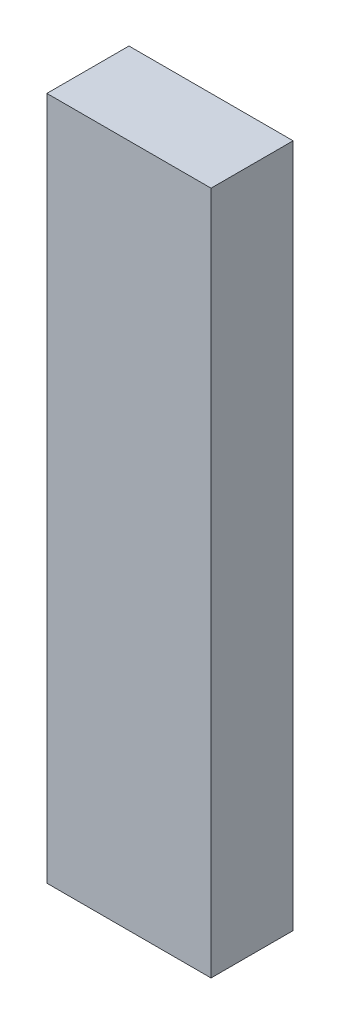
SolidWorks part; units mm, degrees
ref_plane "Front Plane" through (0, 0, 0) normal (0, 0, 1) x (1, 0, 0)
ref_plane "Top Plane" through (0, 0, 0) normal (0, 1, 0) x (1, 0, 0)
ref_plane "Right Plane" through (0, 0, 0) normal (1, 0, 0) x (0, 0, -1)
sketch "Sketch1" plane through (0, 0, 0) normal (0, 1, 0) x (1, 0, 0)
  line L1 (3, -1.5) -> (-3, -1.5)
  line L2 (3, -1.5) -> (3, 1.5)
  line L3 (3, 1.5) -> (-3, 1.5)
  line L4 (-3, -1.5) -> (-3, 1.5)
  line L5 (3, -1.5) -> (-3, 1.5) construction
  line L6 (3, 1.5) -> (-3, -1.5) construction
  point P0 (0, 0)
  dimension "D1" = 6
  dimension "D2" = 3
extrude "Key_6x3x25" add sketch "Sketch1" along normal blind 25
